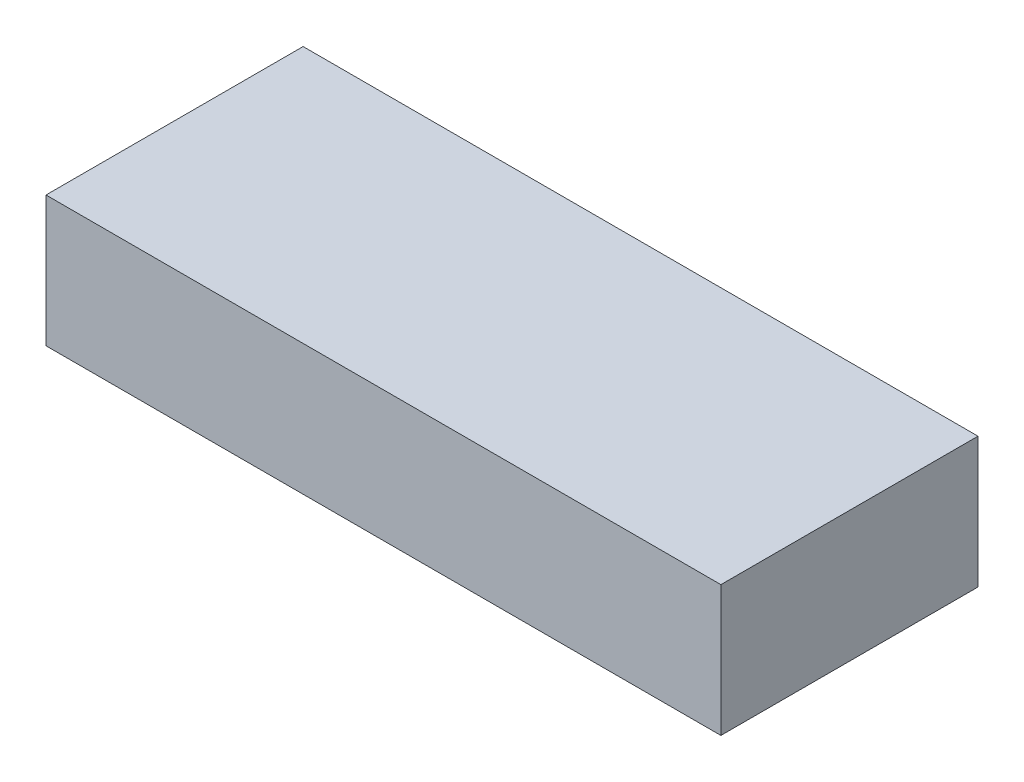
SolidWorks part; units mm, degrees
ref_plane "Front Plane" through (0, 0, 0) normal (0, 0, 1) x (1, 0, 0)
ref_plane "Top Plane" through (0, 0, 0) normal (0, 1, 0) x (1, 0, 0)
ref_plane "Right Plane" through (0, 0, 0) normal (1, 0, 0) x (0, 0, -1)
sketch "草圖1" plane through (0, 0, 0) normal (0, 0, 1) x (1, 0, 0)
  line L0 (-15.5, -3) -> (15.5, -3)
  line L1 (15.5, -3) -> (15.5, 3)
  line L2 (15.5, 3) -> (-15.5, 3)
  line L3 (-15.5, 3) -> (-15.5, -3)
extrude "填料-伸長1" add sketch "草圖1" along normal blind 11.81
